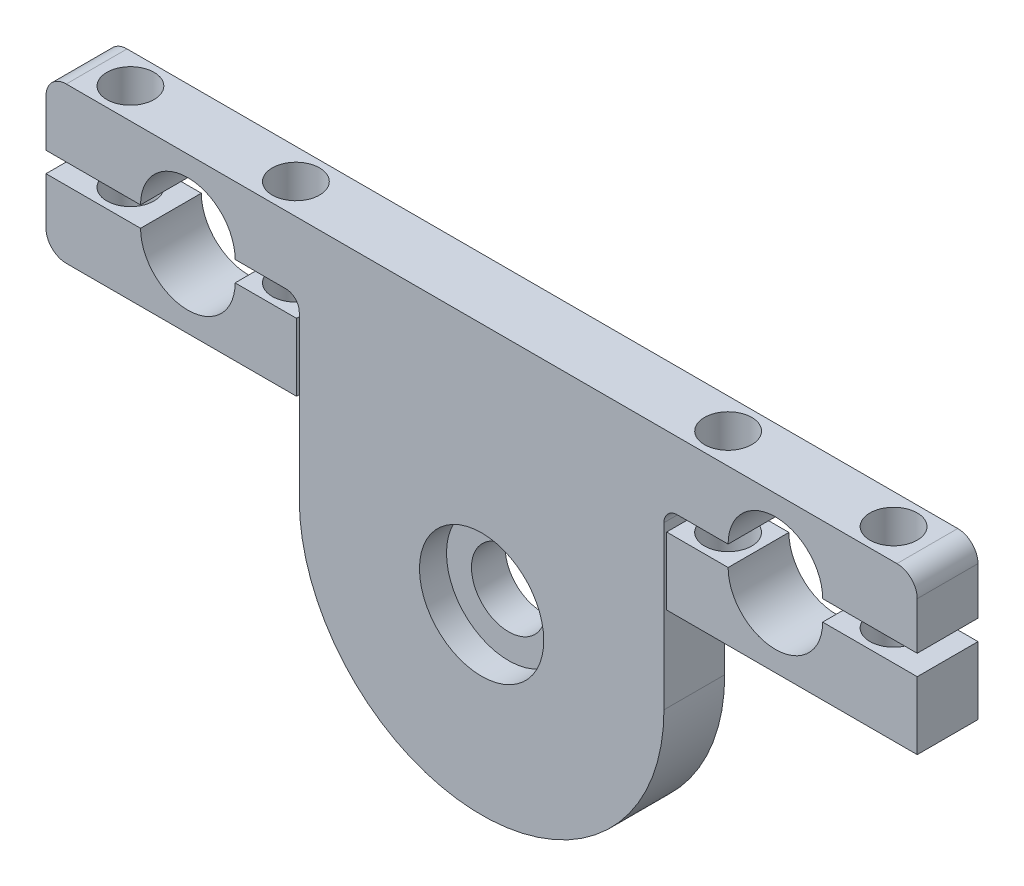
SolidWorks part; units mm, degrees
ref_plane "Front Plane" through (0, 0, 0) normal (0, 0, 1) x (1, 0, 0)
ref_plane "Top Plane" through (0, 0, 0) normal (0, 1, 0) x (1, 0, 0)
ref_plane "Right Plane" through (0, 0, 0) normal (1, 0, 0) x (0, 0, -1)
sketch "草图1" plane through (0, 0, 0) normal (0, 0, 1) x (1, 0, 0)
  line L0 (0, 0) -> (50000, 0) construction
  line L2 (-13.5, 0) -> (13.5, 0)
  line L3 (-13.5, 0) -> (-13.5, 18)
  line L4 (-13.5, 18) -> (13.5, 18)
  line L5 (13.5, 0) -> (13.5, 18)
  circle A0 centre (0, 0) radius 13.5
  circle A1 centre (0, 0) radius 4.6
  dimension "D1" = 27
  dimension "D3" = 9.2
  dimension "D2" = 27
  dimension "D4" = 18
extrude "凸台-拉伸1" add sketch "草图1" along normal blind 4.5 contours L2 A0 | L2 A0 | A0 L5 L4 L3
sketch "草图3" plane through (0, 0, 0) normal (0, 0, -1) x (-1, 0, 0)
  circle A0 centre (0, 0) radius 4.6 construction
  circle A1 centre (0, 0) radius 4.6
extrude "凸台-拉伸2" add sketch "草图3" against normal blind 2.5
sketch "草图4" plane through (0, 0, 0) normal (0, 0, -1) x (-1, 0, 0)
  circle A0 centre (0, 0) radius 2.75
  dimension "D1" = 5.5
extrude "切除-拉伸1" cut sketch "草图4" against normal blind 2.5
sketch "草图5" plane through (13.5, 0, 0) normal (1, 0, 0) x (0, 0, -1)
  line L0 (-4.5, 0) -> (-4.5, 18) construction
  line L1 (-4.5, 18) -> (0, 18)
  line L2 (-4.5, 18) -> (-4.5, 13)
  line L3 (-4.5, 13) -> (0, 13)
  line L4 (0, 18) -> (0, 13)
  line L5 (0, 0) -> (0, 18) construction
  line L6 (-4.5, 18) -> (0, 18) construction
  line L8 (-4.5, 11.5) -> (0, 11.5)
  line L9 (-4.5, 11.5) -> (-4.5, 6.5)
  line L10 (-4.5, 6.5) -> (0, 6.5)
  line L11 (0, 11.5) -> (0, 6.5)
  dimension "D1" = 0
  dimension "D2" = 5
  dimension "D3" = 5
  dimension "D4" = 1.5
extrude "凸台-拉伸3" add sketch "草图5" along normal blind 18.75
sketch "草图6" plane through (0, 0, 0) normal (0, 0, -1) x (-1, 0, 0)
  line L0 (-32.25, 13) -> (-13.5, 13) construction
  line L1 (-13.5, 11.5) -> (-13.5, 13) construction
  line L2 (-32.25, 11.5) -> (-13.5, 11.5) construction
  line L3 (-25.25, 13) -> (-18.25, 13)
  line L4 (-18.25, 11.5) -> (-25.25, 11.5)
  arc A0 (-25.25, 13) -> (-18.25, 13) centre (-21.75, 13) cw
  arc A1 (-18.25, 11.5) -> (-25.25, 11.5) centre (-21.75, 11.5) cw
  line M10 (-13.5, 11.5) -> (-32.25, 11.5)
  dimension "D2" = 3.5
  dimension "D1" = 8.25
extrude "切除-拉伸2" cut sketch "草图6" against normal blind 18.75 contours A1 M10 | A0 L3
sketch "草图7" plane through (0, 18, 0) normal (0, 1, 0) x (1, 0, 0)
  line L0 (32.25, 0) -> (32.25, -4.5) construction
  circle A0 centre (28.25, -2.25) radius 1.75
  point P4 (32.25, -2.25)
  dimension "D2" = 3.5
  dimension "D1" = 4
extrude "切除-拉伸3" cut sketch "草图7" against normal blind 18.75
sketch "草图8" plane through (0, 0, 0) normal (0, 0, -1) x (-1, 0, 0)
  line L0 (0, 0) -> (0, 50000) construction
ref_plane "基准面1" through (0, 0, 0) normal (1, 0, 0) x (0, 0, -1)
sketch "草图9" plane through (0, 18, 0) normal (0, 1, 0) x (1, 0, 0)
  line L0 (32.25, 0) -> (32.25, -4.5) construction
  circle A0 centre (16, -2.25) radius 1.75
  dimension "D1" = 3.5
  dimension "D2" = 16.25
extrude "切除-拉伸8" cut sketch "草图9" against normal blind 20
mirror "镜向3" about plane through (0, 0, 0) normal (1, 0, 0) of "凸台-拉伸3", "切除-拉伸2", "切除-拉伸3", "切除-拉伸8"
sketch "草图13" plane through (0, 0, 4.5) normal (0, 0, 1) x (1, 0, 0)
  line L0 (-13.5, 11.5) -> (-13.5, 6.5)
  line L1 (-13.5, 0) -> (-13.5, 6.5) construction
  line L2 (13.5, 6.5) -> (13.5, 11.5)
extrude "切除-拉伸-薄壁4" cut sketch "草图13" against normal blind 10 thin
fillet "圆角1" radius 1.5 2 edges at (-32.25, 18, 2.25) (32.25, 18, 2.25)
fillet "圆角2" radius 1.5 1 edges at (-32.25, 6.5, 2.25)
fillet "圆角3" radius 1 2 edges at (13.5, 13, 2.25) (-13.5, 13, 2.25)
